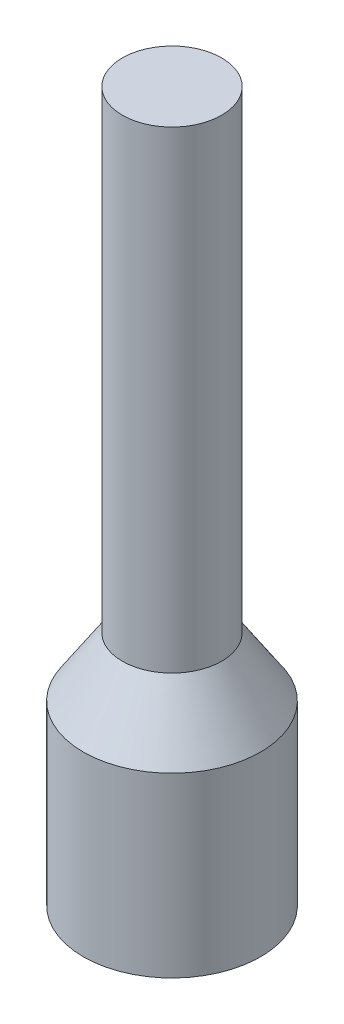
SolidWorks part; units mm, degrees
ref_plane "Front Plane" through (0, 0, 0) normal (0, 0, 1) x (1, 0, 0)
ref_plane "Top Plane" through (0, 0, 0) normal (0, 1, 0) x (1, 0, 0)
ref_plane "Right Plane" through (0, 0, 0) normal (1, 0, 0) x (0, 0, -1)
sketch "Sketch1" plane through (0, 0, 0) normal (0, 0, 1) x (1, 0, 0)
  line L0 (0, 334.4175) -> (0, -39.8304) construction
  line L1 (0, 0) -> (37.5, 0)
  line L2 (37.5, 0) -> (37.5, 75)
  line L3 (37.5, 75) -> (21, 100)
  line L4 (21, 100) -> (21, 300)
  line L5 (21, 300) -> (0, 300)
  line L6 (0, 300) -> (0, 0)
  dimension "D1" = 37.5
  dimension "D2" = 300
  dimension "D3" = 100
  dimension "D4" = 75
  dimension "D5" = 21
revolve "Revolve1" add sketch "Sketch1" angle 360 about L0
